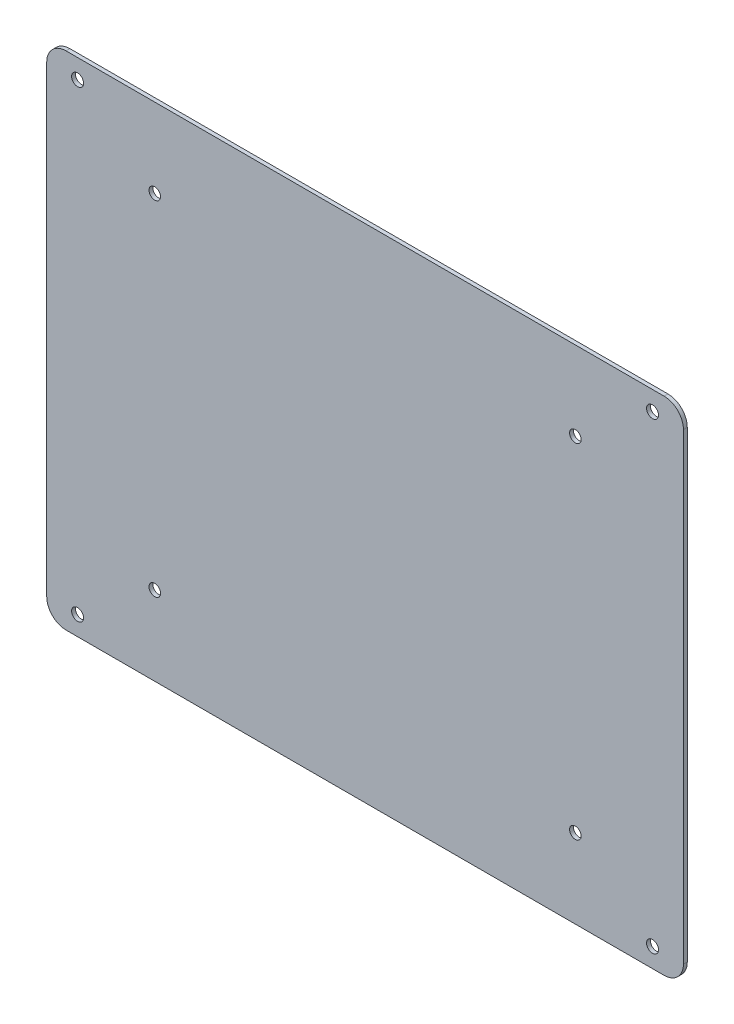
SolidWorks part; units mm, degrees
ref_plane "前视基准面" through (0, 0, 0) normal (0, 0, 1) x (1, 0, 0)
ref_plane "上视基准面" through (0, 0, 0) normal (0, 1, 0) x (1, 0, 0)
ref_plane "右视基准面" through (0, 0, 0) normal (1, 0, 0) x (0, 0, -1)
sketch "草图1" plane through (0, 0, 0) normal (0, 0, 1) x (1, 0, 0)
  line L1 (-77.5, 65) -> (77.5, 65)
  line L2 (-82.5, 60) -> (-82.5, -60)
  line L3 (-77.5, -65) -> (77.5, -65)
  line L4 (82.5, 60) -> (82.5, -60)
  line L5 (-82.5, 65) -> (82.5, -65) construction
  line L6 (-82.5, -65) -> (82.5, 65) construction
  circle A0 centre (-74.5, 60) radius 1.55
  circle A1 centre (74.5, 60) radius 1.55
  circle A2 centre (74.5, -60) radius 1.55
  circle A3 centre (-74.5, -60) radius 1.55
  arc A6 (77.5, 65) -> (82.5, 60) centre (77.5, 60) cw
  arc A7 (77.5, -65) -> (82.5, -60) centre (77.5, -60) ccw
  arc A8 (-82.5, -60) -> (-77.5, -65) centre (-77.5, -60) ccw
  arc A9 (-77.5, 65) -> (-82.5, 60) centre (-77.5, 60) ccw
  point P0 (0, 0)
  point P5 (0, 0)
  point P19 (43.0615, -40.5)
  dimension "D5" = 3.1
  dimension "D7" = 8
  dimension "D10" = 5
  dimension "D12" = 3.1
  dimension "D13" = 3.1
  dimension "D14" = 3.1
  dimension "D1" = 165
  dimension "D2" = 130
  dimension "D3" = 8
  dimension "D4" = 120
  dimension "D6" = 8
  dimension "D8" = 8
extrude "凸台-拉伸1" add sketch "草图1" along normal blind 1
sketch "草图2" plane through (0, 0, 1) normal (0, 0, 1) x (1, 0, 0)
  circle A0 centre (-54.5, 44.5) radius 1.5
  circle A1 centre (-54.5, -44.5) radius 1.5
  circle A2 centre (54.5, -44.5) radius 1.5
  circle A3 centre (54.5, 44.5) radius 1.5
  point P0 (0, 0)
  dimension "D1" = 109
  dimension "D2" = 89
extrude "切除-拉伸1" cut sketch "草图2" against normal blind 10
